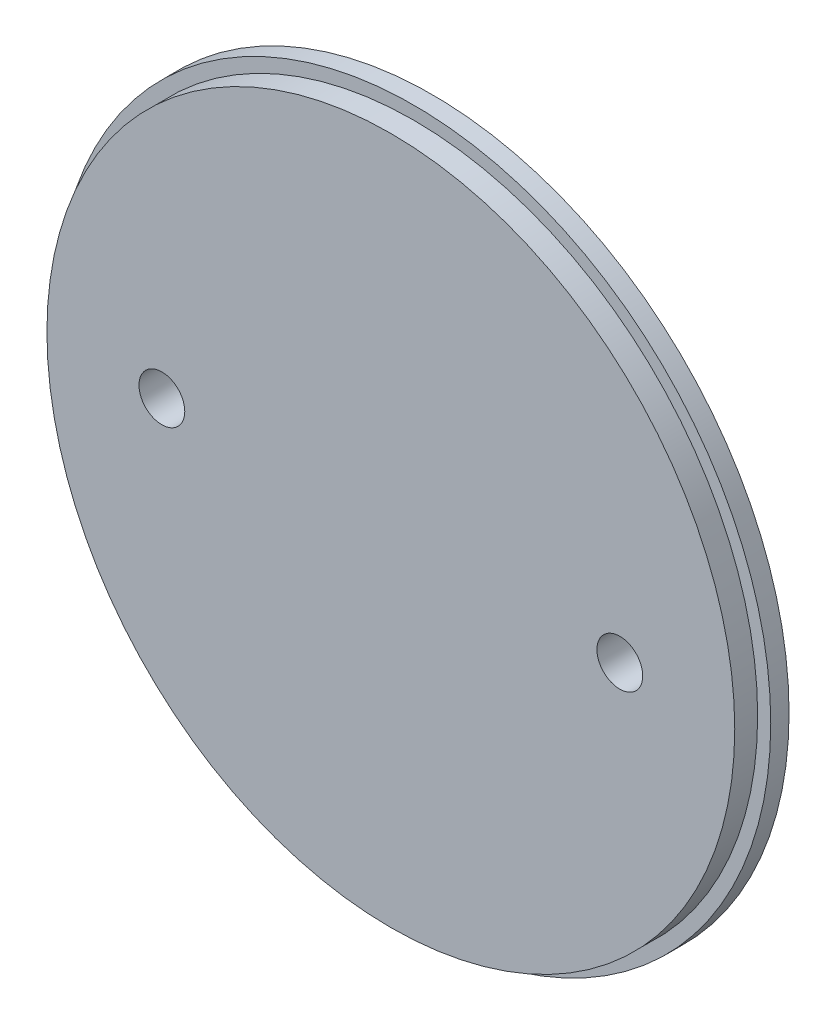
SolidWorks part; units mm, degrees
ref_plane "Front Plane" through (0, 0, 0) normal (0, 0, 1) x (1, 0, 0)
ref_plane "Top Plane" through (0, 0, 0) normal (0, 1, 0) x (1, 0, 0)
ref_plane "Right Plane" through (0, 0, 0) normal (1, 0, 0) x (0, 0, -1)
sketch "Sketch1" plane through (0, 0, 0) normal (0, 0, 1) x (1, 0, 0)
  circle A0 centre (0, 0) radius 49.5046
  dimension "D1" = 99.0092
extrude "Boss-Extrude1" add sketch "Sketch1" along normal blind 2.54
sketch "Sketch2" plane through (0, 0, 2.54) normal (0, 0, 1) x (1, 0, 0)
  circle A0 centre (0, 0) radius 47.6885
  dimension "D1" = 95.377
extrude "Boss-Extrude2" add sketch "Sketch2" along normal blind 3.175
sketch "Sketch3" plane through (0, 0, 5.715) normal (0, 0, 1) x (1, 0, 0)
  circle A0 centre (-31.75, 0) radius 3.175
  circle A1 centre (31.75, 0) radius 3.175
  point P4 (0, 0)
  dimension "D1" = 6.35
  dimension "D2" = 6.35
  dimension "D3" = 63.5
  dimension "D4" = 31.75
extrude "Cut-Extrude1" cut sketch "Sketch3" against normal through all
